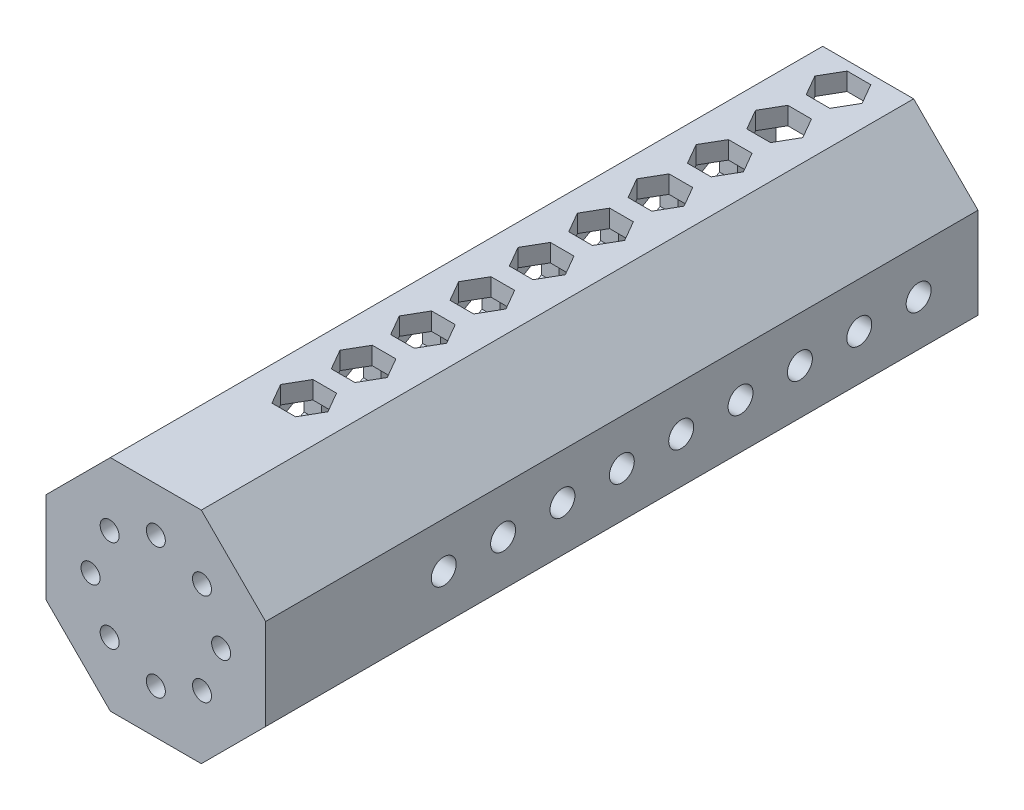
SolidWorks part; units mm, degrees
ref_plane "Alzado" through (0, 0, 0) normal (0, 0, 1) x (1, 0, 0)
ref_plane "Planta" through (0, 0, 0) normal (0, 1, 0) x (1, 0, 0)
ref_plane "Vista lateral" through (0, 0, 0) normal (1, 0, 0) x (0, 0, -1)
sketch "Croquis1" plane through (0, 0, 0) normal (0, 0, 1) x (1, 0, 0)
  line L1 (18.5, -7.663) -> (18.5, 7.663)
  line L2 (18.5, 7.663) -> (7.663, 18.5)
  line L3 (7.663, 18.5) -> (-7.663, 18.5)
  line L4 (-7.663, 18.5) -> (-18.5, 7.663)
  line L5 (-18.5, 7.663) -> (-18.5, -7.663)
  line L6 (-18.5, -7.663) -> (-7.663, -18.5)
  line L7 (-7.663, -18.5) -> (7.663, -18.5)
  line L8 (7.663, -18.5) -> (18.5, -7.663)
  circle A0 centre (0, 0) radius 18.5 construction
  dimension "D1" = 37
extrude "Saliente-Extruir1" add sketch "Croquis1" along normal blind 60
sketch "Croquis8" plane through (0, -18.5, 0) normal (0, -1, 0) x (1, 0, 0)
  line L0 (-7.663, 0) -> (7.663, 0) construction
  circle A0 centre (0, 5) radius 2.1
  point P5 (0, 0)
  dimension "D1" = 4.2
  dimension "D2" = 5
mirror "Simetría1" about plane through (0, 0, 60) normal (0, 0, 1) of "Saliente-Extruir1"
sketch "Croquis6" plane through (0, 0, 120) normal (0, 0, 1) x (1, 0, 0)
  circle A0 centre (0, 11) radius 1.6
  circle A9 centre (7.7782, 7.7782) radius 1.6
  circle A10 centre (11, 0) radius 1.6
  circle A11 centre (7.7782, -7.7782) radius 1.6
  circle A12 centre (0, -11) radius 1.6
  circle A13 centre (-7.7782, -7.7782) radius 1.6
  circle A14 centre (-11, 0) radius 1.6
  circle A15 centre (-7.7782, 7.7782) radius 1.6
  point P2 (12.4724, 4.8162)
  point P3 (0, 0)
  point P4 (0, 0)
  point P19 (0, 0)
  point P22 (0, 0)
  dimension "D1" = 3.2
  dimension "D2" = 11
  dimension "D3" = 8
extrude "Cortar-Extruir5" cut sketch "Croquis6" against normal blind 20
extrude "Cortar-Extruir8" cut sketch "Croquis8" against normal through all
pattern_linear "MatrizL1" count 10 spacing 10 along (0, 0, 1) of "Cortar-Extruir8"
sketch "Croquis9" plane through (18.5, 0, -15) normal (-1, 0, 0) x (0, 0, -1)
  line L1 (-15, 7.663) -> (-15, -7.663) construction
  circle A0 centre (-25, 0) radius 2.1
  point P2 (-48.6813, 0)
  point P3 (0, 0)
  dimension "D1" = 4.2
  dimension "D2" = 10
extrude "Cortar-Extruir11" cut sketch "Croquis9" along normal through all
pattern_linear "MatrizL2" count 9 spacing 10 along (0, 0, 1) of "Cortar-Extruir11"
sketch "Croquis10" plane through (0, 0, 120) normal (0, 0, 1) x (1, 0, 0)
  line L1 (15.4705, -6.491) -> (15.5291, 6.3495)
  line L2 (15.5291, 6.3495) -> (6.491, 15.4705)
  line L3 (6.491, 15.4705) -> (-6.3495, 15.5291)
  line L4 (-6.3495, 15.5291) -> (-15.4705, 6.491)
  line L5 (-15.4705, 6.491) -> (-15.5291, -6.3495)
  line L6 (-15.5291, -6.3495) -> (-6.491, -15.4705)
  line L7 (-6.491, -15.4705) -> (6.3495, -15.5291)
  line L8 (6.3495, -15.5291) -> (15.4705, -6.491)
  circle A0 centre (0, 0) radius 15.5 construction
  dimension "D1" = 31
extrude "Cortar-Extruir12" cut sketch "Croquis10" against normal through all from offset 10 offset against normal yes
sketch "Croquis11" plane through (-18.5, 0, 0) normal (-1, 0, 0) x (0, 0, 1)
  line L1 (90, 3.9837) -> (86.55, 1.9919)
  line L2 (86.55, 1.9919) -> (86.55, -1.9919)
  line L3 (86.55, -1.9919) -> (90, -3.9837)
  line L4 (90, -3.9837) -> (93.45, -1.9919)
  line L5 (93.45, -1.9919) -> (93.45, 1.9919)
  line L6 (93.45, 1.9919) -> (90, 3.9837)
  circle A0 centre (90, 0) radius 3.45 construction
  point P1 (100, 0)
  point P10 (90, 0)
  dimension "D1" = 6.9
extrude "Cortar-Extruir13" cut sketch "Croquis11" against normal blind 10
pattern_linear "MatrizL3" count 9 spacing 10 along (0, 0, -1) of "Cortar-Extruir13"
sketch "Croquis12" plane through (0, 18.5, 0) normal (0, 1, 0) x (1, 0, 0)
  line L1 (3.9837, -5) -> (1.9919, -1.55)
  line L2 (1.9919, -1.55) -> (-1.9919, -1.55)
  line L3 (-1.9919, -1.55) -> (-3.9837, -5)
  line L4 (-3.9837, -5) -> (-1.9919, -8.45)
  line L5 (-1.9919, -8.45) -> (1.9919, -8.45)
  line L6 (1.9919, -8.45) -> (3.9837, -5)
  circle A0 centre (0, -5) radius 3.45 construction
  dimension "D1" = 6.9
extrude "Cortar-Extruir14" cut sketch "Croquis12" against normal blind 10
pattern_linear "MatrizL4" count 10 spacing 10 along (0, 0, 1) of "Cortar-Extruir14"
sketch "Croquis13" plane through (0, 0, 110) normal (0, 0, -1) x (-1, 0, 0)
  line L1 (10.8454, 6.9563) -> (10.0235, 10.0235)
  line L2 (10.0235, 10.0235) -> (6.9563, 10.8454)
  line L3 (6.9563, 10.8454) -> (4.7109, 8.6)
  line L4 (4.7109, 8.6) -> (5.5328, 5.5328)
  line L5 (5.5328, 5.5328) -> (8.6, 4.7109)
  line L6 (8.6, 4.7109) -> (10.8454, 6.9563)
  line L7 (0, 0) -> (32981.7646, 32981.7646) construction
  line L8 (12.5877, -2.75) -> (14.1754, 0)
  line L9 (14.1754, 0) -> (12.5877, 2.75)
  line L10 (12.5877, 2.75) -> (9.4123, 2.75)
  line L11 (9.4123, 2.75) -> (7.8246, 0)
  line L12 (7.8246, 0) -> (9.4123, -2.75)
  line L13 (9.4123, -2.75) -> (12.5877, -2.75)
  line L14 (6.9563, -10.8454) -> (10.0235, -10.0235)
  line L15 (10.0235, -10.0235) -> (10.8454, -6.9563)
  line L16 (10.8454, -6.9563) -> (8.6, -4.7109)
  line L17 (8.6, -4.7109) -> (5.5328, -5.5328)
  line L18 (5.5328, -5.5328) -> (4.7109, -8.6)
  line L19 (4.7109, -8.6) -> (6.9563, -10.8454)
  line L20 (-2.75, -12.5877) -> (0, -14.1754)
  line L21 (0, -14.1754) -> (2.75, -12.5877)
  line L22 (2.75, -12.5877) -> (2.75, -9.4123)
  line L23 (2.75, -9.4123) -> (0, -7.8246)
  line L24 (0, -7.8246) -> (-2.75, -9.4123)
  line L25 (-2.75, -9.4123) -> (-2.75, -12.5877)
  line L26 (-10.8454, -6.9563) -> (-10.0235, -10.0235)
  line L27 (-10.0235, -10.0235) -> (-6.9563, -10.8454)
  line L28 (-6.9563, -10.8454) -> (-4.7109, -8.6)
  line L29 (-4.7109, -8.6) -> (-5.5328, -5.5328)
  line L30 (-5.5328, -5.5328) -> (-8.6, -4.7109)
  line L31 (-8.6, -4.7109) -> (-10.8454, -6.9563)
  line L32 (-12.5877, 2.75) -> (-14.1754, 0)
  line L33 (-14.1754, 0) -> (-12.5877, -2.75)
  line L34 (-12.5877, -2.75) -> (-9.4123, -2.75)
  line L35 (-9.4123, -2.75) -> (-7.8246, 0)
  line L36 (-7.8246, 0) -> (-9.4123, 2.75)
  line L37 (-9.4123, 2.75) -> (-12.5877, 2.75)
  line L38 (-6.9563, 10.8454) -> (-10.0235, 10.0235)
  line L39 (-10.0235, 10.0235) -> (-10.8454, 6.9563)
  line L40 (-10.8454, 6.9563) -> (-8.6, 4.7109)
  line L41 (-8.6, 4.7109) -> (-5.5328, 5.5328)
  line L42 (-5.5328, 5.5328) -> (-4.7109, 8.6)
  line L43 (-4.7109, 8.6) -> (-6.9563, 10.8454)
  line L44 (2.75, 12.5877) -> (0, 14.1754)
  line L45 (0, 14.1754) -> (-2.75, 12.5877)
  line L46 (-2.75, 12.5877) -> (-2.75, 9.4123)
  line L47 (-2.75, 9.4123) -> (0, 7.8246)
  line L48 (0, 7.8246) -> (2.75, 9.4123)
  line L49 (2.75, 9.4123) -> (2.75, 12.5877)
  circle A0 centre (7.7782, 7.7782) radius 2.75 construction
  circle A1 centre (11, 0) radius 2.75 construction
  circle A2 centre (7.7782, -7.7782) radius 2.75 construction
  circle A3 centre (0, -11) radius 2.75 construction
  circle A4 centre (-7.7782, -7.7782) radius 2.75 construction
  circle A5 centre (-11, 0) radius 2.75 construction
  circle A6 centre (-7.7782, 7.7782) radius 2.75 construction
  circle A7 centre (0, 11) radius 2.75 construction
  point P70 (0, 0)
  dimension "D1" = 5.5
  dimension "D2" = 8
extrude "Cortar-Extruir15" cut sketch "Croquis13" against normal blind 4
